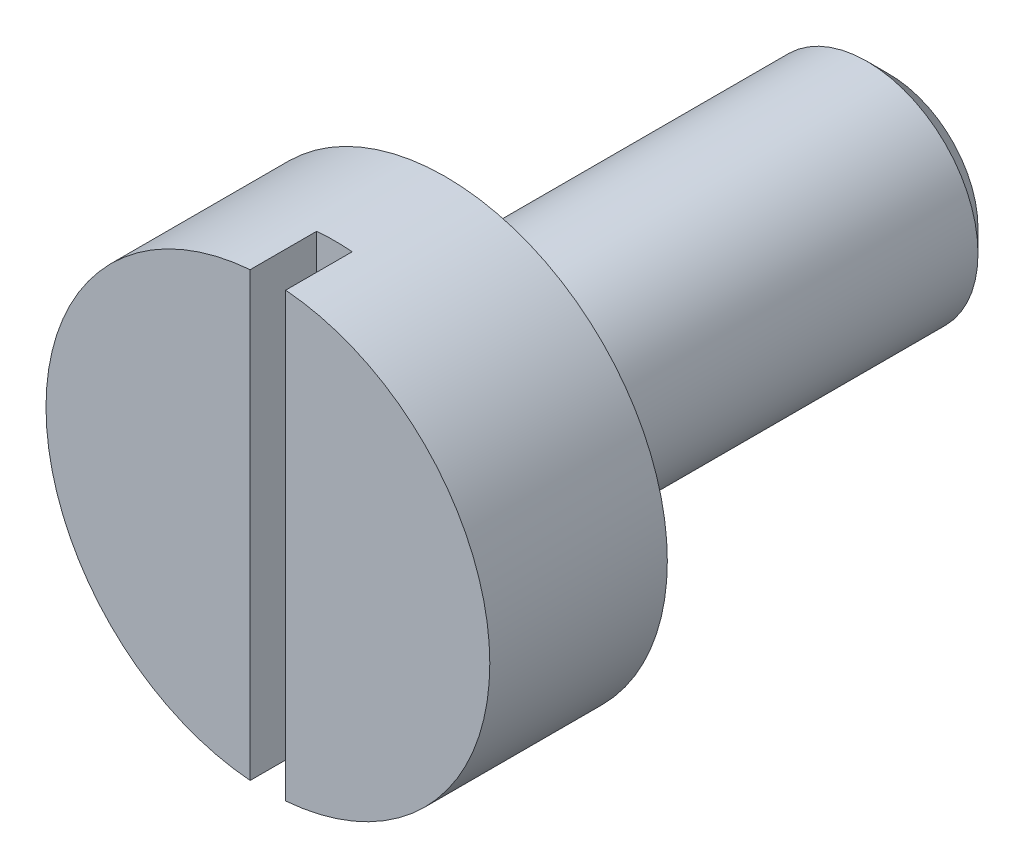
SolidWorks part; units mm, degrees
ref_plane "Спереди" through (0, 0, 0) normal (0, 0, 1) x (1, 0, 0)
ref_plane "Сверху" through (0, 0, 0) normal (0, 1, 0) x (1, 0, 0)
ref_plane "Справа" through (0, 0, 0) normal (1, 0, 0) x (0, 0, -1)
sketch "Эскиз1" plane through (0, 0, 0) normal (0, 0, 1) x (1, 0, 0)
  circle A0 centre (0, 0) radius 2.5
  dimension "D1" = 5
extrude "Вытянуть1" add sketch "Эскиз1" along normal blind 10
sketch "Эскиз2" plane through (0, 0, 10) normal (0, 0, 1) x (1, 0, 0)
  circle A0 centre (0, 0) radius 5
  dimension "D1" = 10
extrude "Вытянуть2" add sketch "Эскиз2" along normal blind 4
sketch "Эскиз3" plane through (0, 0, 14) normal (0, 0, 1) x (1, 0, 0)
  line L0 (0, 1.7974) -> (0, -1.0725) construction
  line L1 (-0.4, -5.6141) -> (0.4, -5.6141)
  line L2 (-0.4, -5.6141) -> (-0.4, 5.7916)
  line L3 (-0.4, 5.7916) -> (0.4, 5.7916)
  line L4 (0.4, -5.6141) -> (0.4, 5.7916)
  dimension "D1" = 0.8
extrude "Вырез-Вытянуть1" cut sketch "Эскиз3" against normal blind 1.5
chamfer "Фаска1" distance 0.5 angle 45
